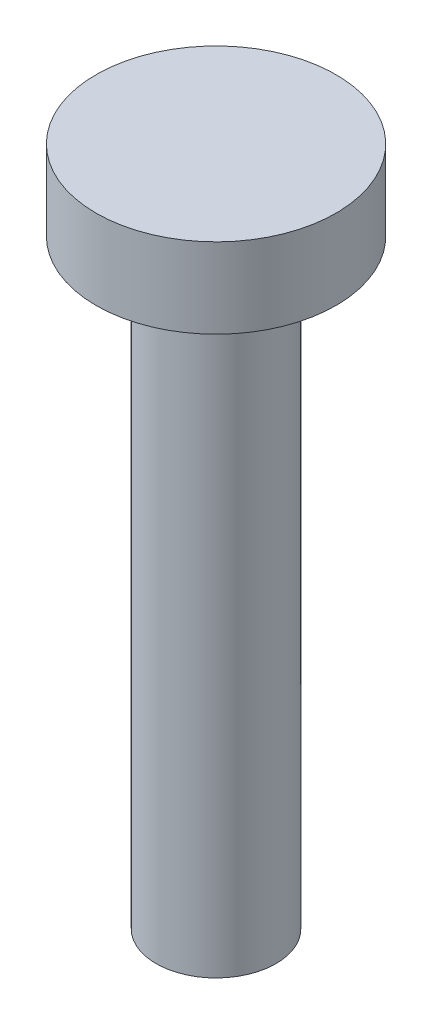
SolidWorks part; units mm, degrees
ref_plane "Plan de face" through (0, 0, 0) normal (0, 0, 1) x (1, 0, 0)
ref_plane "Plan de dessus" through (0, 0, 0) normal (0, 1, 0) x (1, 0, 0)
ref_plane "Plan de droite" through (0, 0, 0) normal (1, 0, 0) x (0, 0, -1)
sketch "Esquisse2" plane through (0, 0, 0) normal (0, 1, 0) x (1, 0, 0)
  circle A0 centre (0, 0) radius 30
  dimension "D1" = 60
extrude "Boss.-Extru.2" add sketch "Esquisse2" along normal blind 20 contours A0
sketch "Esquisse3" plane through (0, 0, 0) normal (0, -1, 0) x (1, 0, 0)
  circle A0 centre (0, 0) radius 15
  dimension "D1" = 30
extrude "Boss.-Extru.3" add sketch "Esquisse3" along normal blind 150
ref_plane "Plan1" through (0, -60, 0) normal (0, 1, 0) x (1, 0, 0)
sketch "Esquisse4" plane through (0, -60, 0) normal (0, 1, 0) x (1, 0, 0)
  circle A0 centre (0, 0) radius 15
  dimension "D1" = 30
curve "Hélice/Spirale1" pitch 4 height 95 turns 23.75
